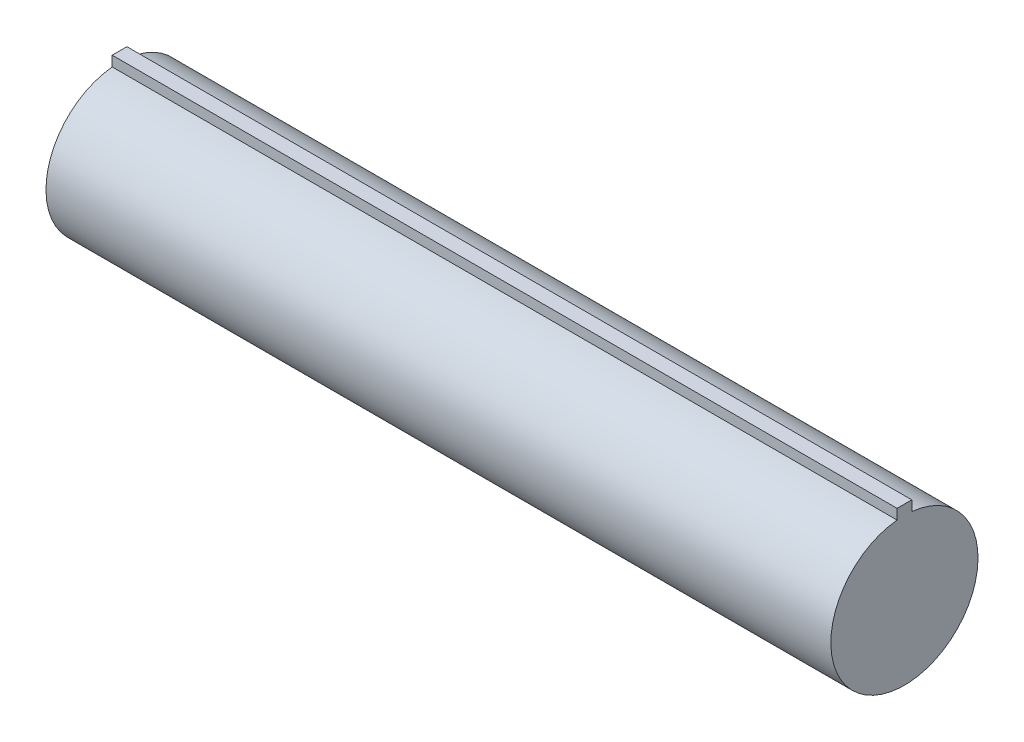
SolidWorks part; units mm, degrees
ref_plane "前视基准面" through (0, 0, 0) normal (0, 0, 1) x (1, 0, 0)
ref_plane "上视基准面" through (0, 0, 0) normal (0, 1, 0) x (1, 0, 0)
ref_plane "右视基准面" through (0, 0, 0) normal (1, 0, 0) x (0, 0, -1)
other "Configuration Table"
sketch "草图1" plane through (0, 0, 0) normal (1, 0, 0) x (0, 0, -1)
  line L1 (-1.5, 0) -> (1.5, 0)
  line L2 (-1.5, 0) -> (-1.5, 17)
  line L3 (-1.5, 17) -> (1.5, 17)
  line L4 (1.5, 0) -> (1.5, 17)
  circle A0 centre (0, 0) radius 15
  point P7 (0, 0)
  dimension "D1" = 30
  dimension "D2" = 3
  dimension "D3" = 17
extrude "凸台-拉伸1" add sketch "草图1" along normal blind 160 from offset 80 contours L2 A0 L4 L1 | A0 L4 L3 L2 | L4 A0 L2 L1
